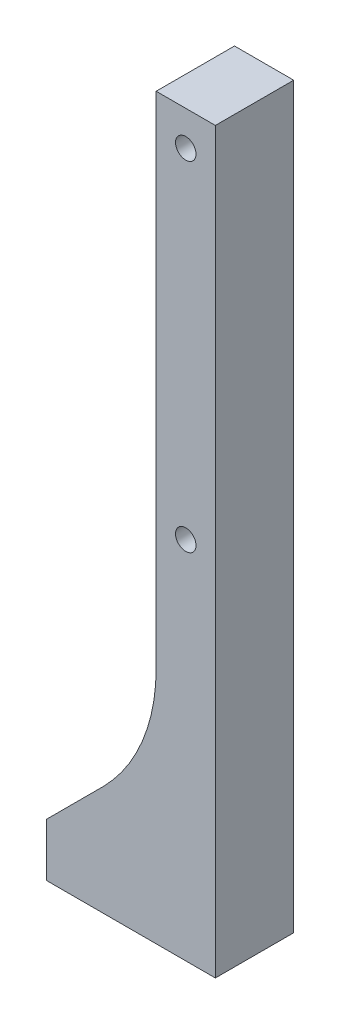
SolidWorks part; units mm, degrees
ref_plane "Front Plane" through (0, 0, 0) normal (0, 0, 1) x (1, 0, 0)
ref_plane "Top Plane" through (0, 0, 0) normal (0, 1, 0) x (1, 0, 0)
ref_plane "Right Plane" through (0, 0, 0) normal (1, 0, 0) x (0, 0, -1)
sketch "Sketch1" plane through (0, 0, 0) normal (0, 1, 0) x (1, 0, 0)
  line L0 (-3.25, -3.25) -> (3.25, -3.25)
  line L1 (-3.25, -3.25) -> (-3.25, 3.25)
  line L2 (3.25, -3.25) -> (3.25, 3.25)
  line L3 (-3.25, 3.25) -> (3.25, 3.25)
  line L4 (-3.25, -3.25) -> (3.25, 3.25) construction
  line L5 (3.25, -3.25) -> (-3.25, 3.25) construction
  circle A0 centre (0, 0) radius 1.5
  point P1 (0, 0)
  dimension "D3" = 3
  dimension "D1" = 6.5
  dimension "D2" = 6.5
extrude "Boss-Extrude1" add sketch "Sketch1" along normal blind 5.8
sketch "Sketch2" plane through (0, 0, 3.25) normal (0, 0, 1) x (1, 0, 0)
  line L1 (3.25, 0) -> (-3.25, 0)
  line L2 (3.25, 0) -> (3.25, 5.8)
  line L3 (3.25, 5.8) -> (-3.25, 5.8)
  line L4 (-3.25, 0) -> (-3.25, 5.8)
extrude "Boss-Extrude2" add sketch "Sketch2" along normal blind 8.85
sketch "Sketch6" plane through (3.25, 0, 0) normal (1, 0, 0) x (0, 0, -1)
  line L0 (-12.1, 5.8) -> (-3.25, 5.8)
  line L1 (-12.1, 5.8) -> (3.25, 5.8) construction
  line L3 (-3.25, 5.8) -> (-12.1, 5.8)
  line L4 (-3.25, 5.8) -> (-3.25, 0)
  line L5 (-3.25, 0) -> (-12.1, 0)
  line L6 (-12.1, 5.8) -> (-12.1, 0)
  line M2 (-12.1, 0) -> (3.25, 0)
  line M4 (3.25, 5.8) -> (-12.1, 5.8)
  line M5 (-12.1, 5.8) -> (-12.1, 0)
  dimension "D1" = 8.85
extrude "Boss-Extrude6" add sketch "Sketch6" along normal blind 12.06 contours L4 M4 M5 M2
sketch "Sketch7" plane through (0, 5.8, 0) normal (0, 1, 0) x (1, 0, 0)
  line L0 (15.31, -3.25) -> (8.81, -3.25)
  line L1 (15.31, -3.25) -> (3.25, -3.25) construction
  line L3 (15.31, -12.1) -> (8.81, -12.1)
  line L4 (15.31, -12.1) -> (15.31, -3.25)
  line L5 (15.31, -3.25) -> (8.81, -3.25)
  line L6 (8.81, -12.1) -> (8.81, -3.25)
  line M4 (-3.25, -12.1) -> (15.31, -12.1)
  line M5 (15.31, -12.1) -> (15.31, -3.25)
  line M6 (15.31, -3.25) -> (3.25, -3.25)
  dimension "D1" = 6.5
extrude "Boss-Extrude7" add sketch "Sketch7" along normal blind 75.25 contours L6 M4 M5 M6
sketch "Sketch8" plane through (0, 0, 12.1) normal (0, 0, 1) x (1, 0, 0)
  line L0 (-3.25, 5.8) -> (8.81, 5.8)
  line L1 (8.81, 5.8) -> (8.81, 17.86)
  line L2 (8.81, 81.05) -> (8.81, 5.8) construction
  line L3 (-3.25, 5.8) -> (8.81, 17.86)
  dimension "D1" = 12.06
extrude "Boss-Extrude8" add sketch "Sketch8" against normal up to surface (8.85 mm away) up to face at (9.1233, 28.95, 3.25)
fillet "Fillet3" radius 20 1 edges at (8.81, 17.86, 7.675)
sketch "Sketch10" plane through (0, 0, 12.1) normal (0, 0, 1) x (1, 0, 0)
  line L0 (12.06, 81.05) -> (12.06, 77.25)
  line L1 (8.81, 81.05) -> (15.31, 81.05) construction
  line L2 (12.06, 77.25) -> (12.06, 40.05)
  circle A0 centre (12.06, 77.25) radius 1.125
  circle A1 centre (12.06, 40.05) radius 1.125
  dimension "D2" = 2.25
  dimension "D4" = 2.25
  dimension "D1" = 3.8
  dimension "D3" = 37.2
extrude "Cut-Extrude1" cut sketch "Sketch10" against normal through all contours A0 | A1
sketch "Sketch11" plane through (0, 0, 3.25) normal (0, 0, -1) x (-1, 0, 0)
  line L1 (-12.06, 79.5) -> (-14.0086, 78.375)
  line L2 (-14.0086, 78.375) -> (-14.0086, 76.125)
  line L3 (-14.0086, 76.125) -> (-12.06, 75)
  line L4 (-12.06, 75) -> (-10.1114, 76.125)
  line L5 (-10.1114, 76.125) -> (-10.1114, 78.375)
  line L6 (-10.1114, 78.375) -> (-12.06, 79.5)
  line L13 (-12.06, 42.3) -> (-14.0086, 41.175)
  line L14 (-14.0086, 41.175) -> (-14.0086, 38.925)
  line L15 (-14.0086, 38.925) -> (-12.06, 37.8)
  line L16 (-12.06, 37.8) -> (-10.1114, 38.925)
  line L17 (-10.1114, 38.925) -> (-10.1114, 41.175)
  line L18 (-10.1114, 41.175) -> (-12.06, 42.3)
  circle A0 centre (-12.06, 77.25) radius 2.25
  circle A1 centre (-12.06, 77.25) radius 1.9486 construction
  circle A2 centre (-12.06, 40.05) radius 2.25
  circle A3 centre (-12.06, 40.05) radius 1.9486 construction
  circle M1 centre (-12.06, 77.25) radius 1.125
  circle M18 centre (-12.06, 40.05) radius 1.125
  dimension "D1" = 4.5
  dimension "D2" = 4.5
extrude "Cut-Extrude2" cut sketch "Sketch11" against normal blind 2 contours L5 L6 L1 L2 L3 L4 M1 | L17 L18 L13 L14 L15 L16 M18
ref_plane "Plane2" through (15.31, 0, 0) normal (1, 0, 0) x (0, 0, -1)
sketch "Sketch13" plane through (0, 0, 0) normal (0, -1, 0) x (-1, 0, 0)
  line L0 (-3.25, -3.25) -> (-3.25, -3.5)
  line L1 (-15.31, -12.1) -> (-15.31, -3.25) construction
  line L2 (-3.25, -3.5) -> (-15.31, -3.5)
  line L3 (-3.25, -3.5) -> (-3.25, -3.25)
  line L4 (-3.25, -3.25) -> (-15.31, -3.25)
  line L5 (-15.31, -3.5) -> (-15.31, -3.25)
  line L6 (-15.31, -3.25) -> (-3.25, -3.25) construction
  line M4 (-3.25, -3.25) -> (-15.31, -3.25)
  line M5 (-15.31, -3.25) -> (-15.31, -12.1)
  dimension "D1" = 0.25
extrude "Cut-Extrude4" cut sketch "Sketch13" against normal through all contours L2 L0 M4 M5
sketch "Sketch14" plane through (0, 5.8, 0) normal (0, 1, 0) x (1, 0, 0)
  line L0 (3.25, -3.25) -> (3.25, -3.5)
  line L2 (3.25, -3.5) -> (-3.25, -3.5)
  line L3 (3.25, -3.5) -> (3.25, -3.25)
  line L4 (3.25, -3.25) -> (-3.25, -3.25)
  line L5 (-3.25, -3.5) -> (-3.25, -3.25)
  line M2 (-3.25, -3.25) -> (3.25, -3.25)
  dimension "D1" = 0.25
extrude "Cut-Extrude5" cut sketch "Sketch14" along normal through all contours L5 L2 L0 M2
